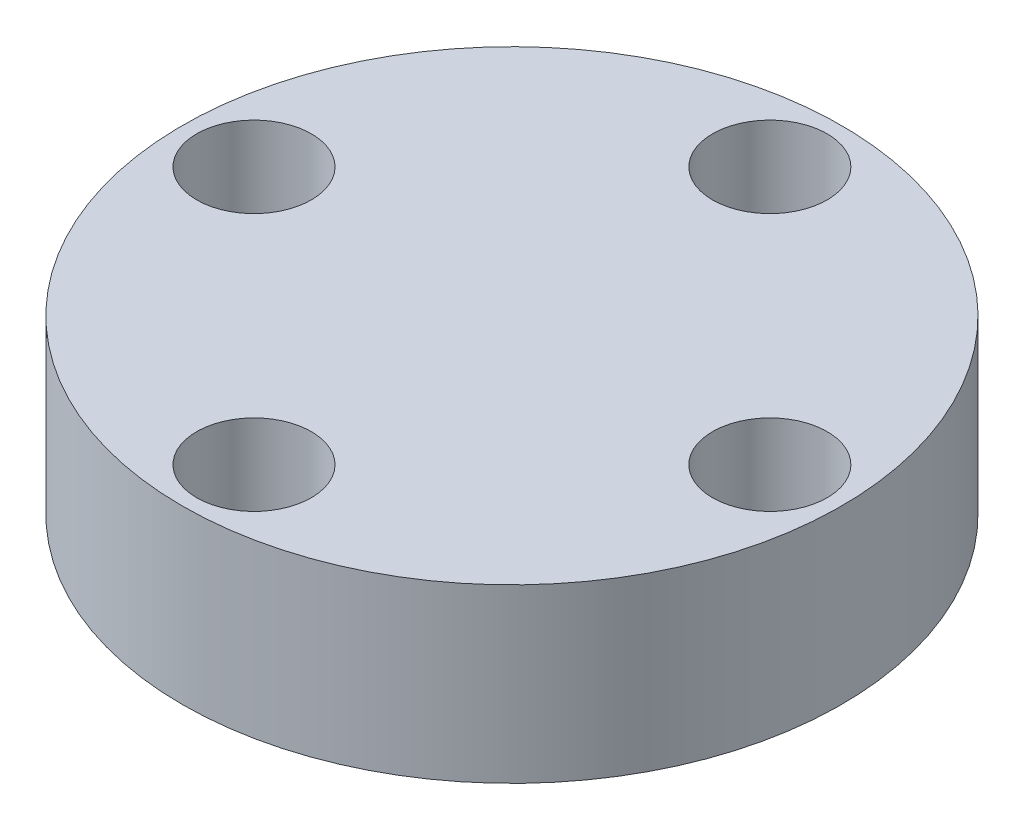
SolidWorks part; units mm, degrees
ref_plane "前视基准面" through (0, 0, 0) normal (0, 0, 1) x (1, 0, 0)
ref_plane "上视基准面" through (0, 0, 0) normal (0, 1, 0) x (1, 0, 0)
ref_plane "右视基准面" through (0, 0, 0) normal (1, 0, 0) x (0, 0, -1)
sketch "草图1" plane through (0, 0, 0) normal (0, 1, 0) x (1, 0, 0)
  circle A0 centre (0, 0) radius 5.75
  dimension "D1" = 11.5
extrude "凸台-拉伸1" add sketch "草图1" along normal blind 3
sketch "草图2" plane through (0, 3, 0) normal (0, 1, 0) x (1, 0, 0)
  circle A0 centre (0, 0) radius 4.5 construction
  circle A1 centre (0, 4.5) radius 1
  circle A2 centre (4.5, 0) radius 1
  circle A3 centre (0, -4.5) radius 1
  circle A4 centre (-4.5, 0) radius 1
  dimension "D1" = 9
  dimension "D2" = 2
extrude "切除-拉伸2" cut sketch "草图2" against normal blind 3
